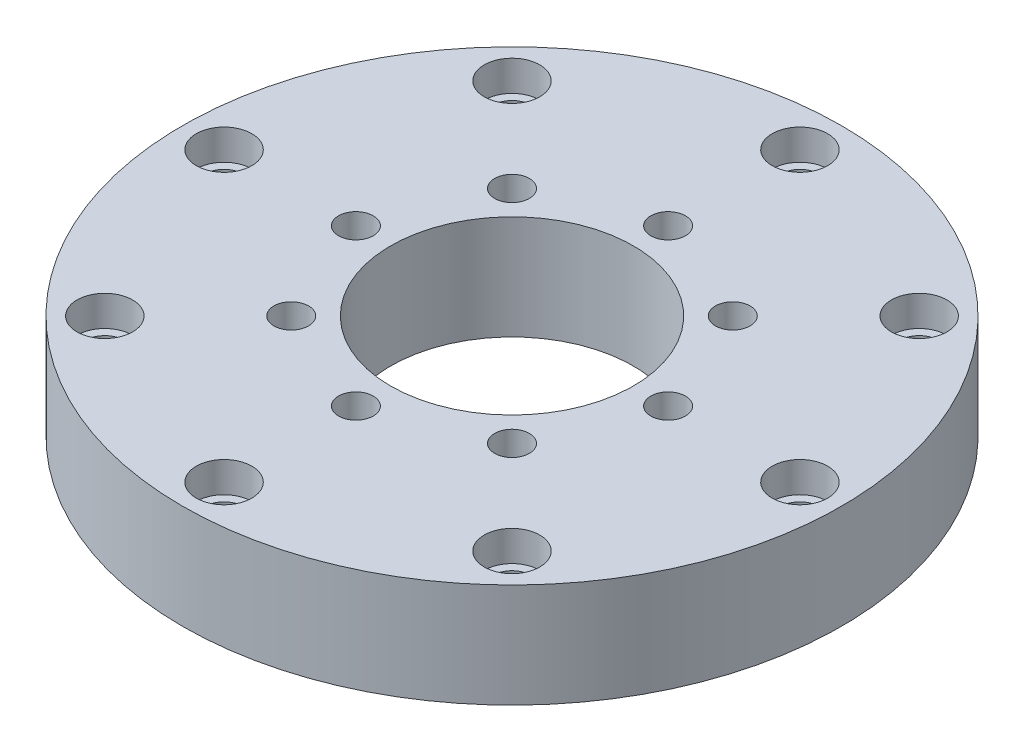
SolidWorks part; units mm, degrees
ref_plane "Front Plane" through (0, 0, 0) normal (0, 0, 1) x (1, 0, 0)
ref_plane "Top Plane" through (0, 0, 0) normal (0, 1, 0) x (1, 0, 0)
ref_plane "Right Plane" through (0, 0, 0) normal (1, 0, 0) x (0, 0, -1)
sketch "Sketch1" plane through (0, 0, 0) normal (0, 1, 0) x (1, 0, 0)
  circle A0 centre (0, 0) radius 47.5
  circle A1 centre (0, 0) radius 17.5
  circle A2 centre (0, 0) radius 22.5 construction
  circle A3 centre (0, 0) radius 41.5 construction
  circle A4 centre (0, 41.5) radius 2.75
  circle A5 centre (29.3449, 29.3449) radius 2.75
  circle A6 centre (41.5, 0) radius 2.75
  circle A7 centre (29.3449, -29.3449) radius 2.75
  circle A8 centre (0, -41.5) radius 2.75
  circle A9 centre (-29.3449, -29.3449) radius 2.75
  circle A10 centre (-41.5, 0) radius 2.75
  circle A11 centre (-29.3449, 29.3449) radius 2.75
  circle A12 centre (0, 22.5) radius 2.5
  circle A13 centre (0, 0) radius 22.5 construction
  circle A14 centre (15.9099, 15.9099) radius 2.5
  circle A15 centre (0, 0) radius 22.5 construction
  circle A16 centre (22.5, 0) radius 2.5
  circle A17 centre (0, 0) radius 22.5 construction
  circle A18 centre (15.9099, -15.9099) radius 2.5
  circle A19 centre (0, 0) radius 22.5 construction
  circle A20 centre (0, -22.5) radius 2.5
  circle A21 centre (0, 0) radius 22.5 construction
  circle A22 centre (-15.9099, -15.9099) radius 2.5
  circle A23 centre (0, 0) radius 22.5 construction
  circle A24 centre (-22.5, 0) radius 2.5
  circle A25 centre (0, 0) radius 22.5 construction
  circle A26 centre (-15.9099, 15.9099) radius 2.5
  point P24 (0, 0)
  point P26 (0, 0)
  point P27 (0, 0)
  point P48 (0, 0)
  point P49 (0, 0)
  point P50 (0, 0)
  point P51 (-69.2711, 48.4959)
  point P52 (0, 0)
  point P53 (0, 0)
  dimension "D1" = 95
  dimension "D2" = 35
  dimension "D3" = 45
  dimension "D4" = 83
  dimension "D5" = 5.5
  dimension "D7" = 5
  dimension "D6" = 8
  dimension "D8" = 8
extrude "Boss-Extrude1" add sketch "Sketch1" along normal blind 15
hole_wizard "CBORE for M5 Hex Head Bolt4" positions "3DSketch7" profile "Sketch6" counterbore size "M5" standard "ANSI Metric" end condition through all
sketch3d "3DSketch7"
  line L0 (0, 15, -41.5) -> (0, 0, -41.5) construction
  line L1 (29.3449, 15, -29.3449) -> (29.3449, 0, -29.3449) construction
  line L2 (41.5, 15, 0) -> (41.5, 0, 0) construction
  line L3 (29.3449, 15, 29.3449) -> (29.3449, 0, 29.3449) construction
  line L4 (0, 15, 41.5) -> (0, 0, 41.5) construction
  line L5 (-29.3449, 15, 29.3449) -> (-29.3449, 0, 29.3449) construction
  line L6 (-41.5, 15, 0) -> (-41.5, 0, 0) construction
  line L7 (-29.3449, 15, -29.3449) -> (-29.3449, 0, -29.3449) construction
  point P0 (0, 15, -41.5)
  point P5 (29.3449, 15, -29.3449)
  point P9 (41.5, 15, 0)
  point P13 (29.3449, 15, 29.3449)
  point P17 (0, 15, 41.5)
  point P21 (-29.3449, 15, 29.3449)
  point P25 (-41.5, 15, 0)
  point P29 (-29.3449, 15, -29.3449)
sketch "Sketch6" plane through (0, 15, -41.5) normal (1, 0, 0) x (0, 0, 1)
  line L0 (0, 0) -> (0, 15)
  line L1 (0, 15) -> (2.25, 15)
  line L3 (2.25, 15) -> (2.25, 4.4)
  line L4 (2.25, 4.4) -> (4, 4.4)
  line L5 (4, 4.4) -> (4, 0)
  line L7 (4, 0) -> (0, 0)
  line L11 (0, -6.35) -> (0, 107.95) construction
  dimension "Thru Hole Dia." = 4.5
  dimension "Thru Hole Depth" = 15
  dimension "C'Bore Dia." = 8
  dimension "C'Bore Depth" = 4.4
